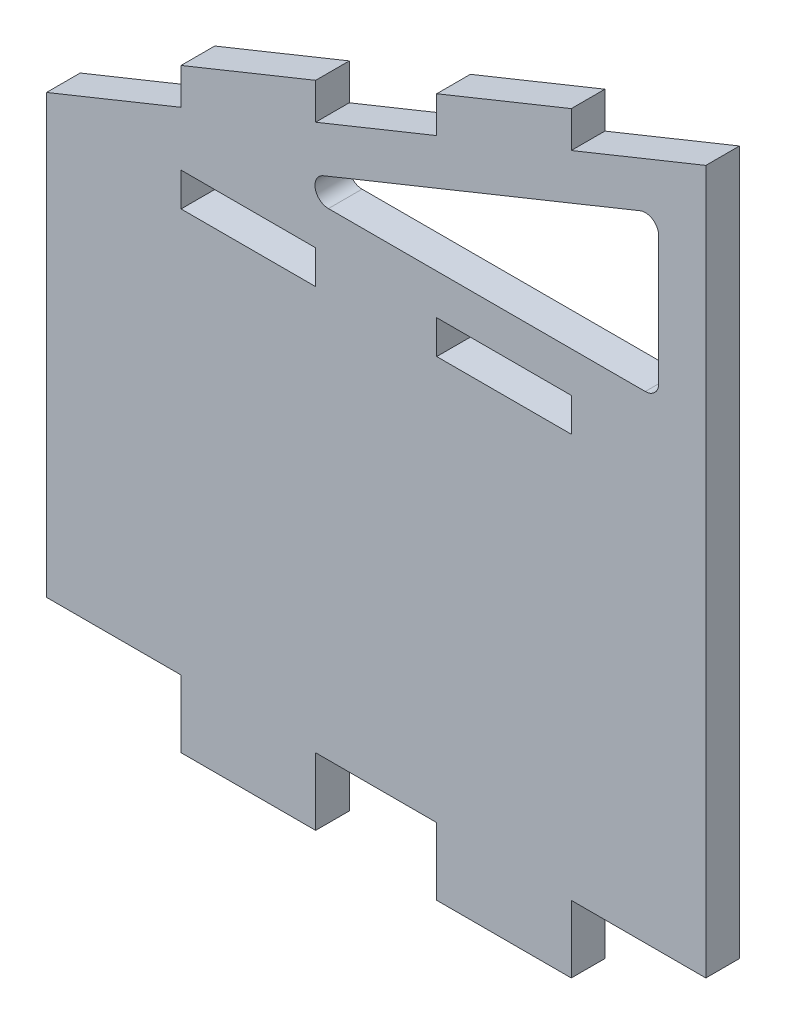
SolidWorks part; units mm, degrees
material "Beech"
ref_plane "Front" through (0, 0, 0) normal (0, 0, 1) x (1, 0, 0)
ref_plane "Top" through (0, 0, 0) normal (0, 1, 0) x (1, 0, 0)
ref_plane "Right" through (0, 0, 0) normal (1, 0, 0) x (0, 0, -1)
sketch "Sketch1" plane through (0, 0, 0) normal (0, 0, 1) x (1, 0, 0)
  line L0 (-24.5, -25) -> (24.5, -25) construction
  line L1 (-24.5, -30) -> (24.5, -30) construction
  line L2 (-24.5, -30) -> (-24.5, 30) construction
  line L3 (-24.5, 30) -> (24.5, 30) construction
  line L4 (24.5, -30) -> (24.5, 30) construction
  line L5 (-24.5, -30) -> (24.5, 30) construction
  line L6 (-24.5, 30) -> (24.5, -30) construction
  line L7 (24.5, 30) -> (-24.5, 10.1965) construction
  line L8 (24.5, 27.3035) -> (-24.5, 7.5) construction
  line L9 (24.5, 7.5) -> (-24.5, 7.5) construction
  line L10 (-24.5, 5) -> (24.5, 5) construction
  line L11 (-24.5, -25) -> (-14.5, -25)
  line L12 (-14.5, -25) -> (-14.5, -30)
  line L13 (-14.5, -30) -> (-4.5, -30)
  line L14 (-4.5, -30) -> (-4.5, -25)
  line L15 (-4.5, -25) -> (4.5, -25)
  line L16 (4.5, -25) -> (4.5, -30)
  line L17 (4.5, -30) -> (14.5, -30)
  line L18 (14.5, -30) -> (14.5, -25)
  line L19 (14.5, -25) -> (24.5, -25)
  line L20 (24.5, -25) -> (24.5, 27.3035)
  line L21 (24.5, 27.3035) -> (14.5, 23.262)
  line L22 (14.5, 23.262) -> (14.5, 25.9585)
  line L23 (14.5, 25.9585) -> (4.5, 21.9169)
  line L24 (4.5, 21.9169) -> (4.5, 19.2205)
  line L25 (4.5, 19.2205) -> (-4.5, 15.5831)
  line L26 (-4.5, 15.5831) -> (-4.5, 18.2795)
  line L27 (-4.5, 18.2795) -> (-14.5, 14.238)
  line L28 (-14.5, 14.238) -> (-14.5, 11.5415)
  line L29 (-14.5, 11.5415) -> (-24.5, 7.5)
  line L30 (-24.5, 7.5) -> (-24.5, -25)
  line L31 (-8.6917, 10.5) -> (21, 10.5) construction
  line L32 (-14.5, 5) -> (-4.5, 5)
  line L33 (-14.5, 5) -> (-14.5, 7.5)
  line L34 (-14.5, 7.5) -> (-4.5, 7.5)
  line L35 (-4.5, 5) -> (-4.5, 7.5)
  line L36 (-14.5, 5) -> (-4.5, 7.5) construction
  line L37 (-14.5, 7.5) -> (-4.5, 5) construction
  line L38 (4.5, 5) -> (14.5, 5)
  line L39 (4.5, 5) -> (4.5, 7.5)
  line L40 (4.5, 7.5) -> (14.5, 7.5)
  line L41 (14.5, 5) -> (14.5, 7.5)
  line L42 (4.5, 5) -> (14.5, 7.5) construction
  line L43 (4.5, 7.5) -> (14.5, 5) construction
  line L44 (21, 10.5) -> (21, 22.5) construction
  line L45 (21, 22.5) -> (-8.6917, 10.5) construction
  line L49 (21, 21.0173) -> (21, 11.5)
  line L50 (20, 10.5) -> (-3.5486, 10.5)
  line L51 (-3.9233, 12.4271) -> (19.6253, 21.9444)
  arc A3 (21, 11.5) -> (20, 10.5) centre (20, 11.5) cw
  arc A4 (21, 21.0173) -> (19.6253, 21.9444) centre (20, 21.0173) ccw
  arc A5 (-3.9233, 12.4271) -> (-3.5486, 10.5) centre (-3.5486, 11.5) ccw
  point P0 (0, 0)
  point P34 (-9.5, 6.25)
  point P39 (9.5, 6.25)
  point P52 (0, 0)
  point P53 (-8.6917, 10.5)
  dimension "D10" = 12
  dimension "D11" = 1
  dimension "D1" = 49
  dimension "D2" = 60
  dimension "D3" = 2.5
  dimension "D4" = 37.5
  dimension "D5" = 2.5
  dimension "D6" = 5
  dimension "D7" = 9
  dimension "D8" = 3.5
  dimension "D9" = 3
extrude "Boss-Extrude1" add sketch "Sketch1" along normal blind 2.5
